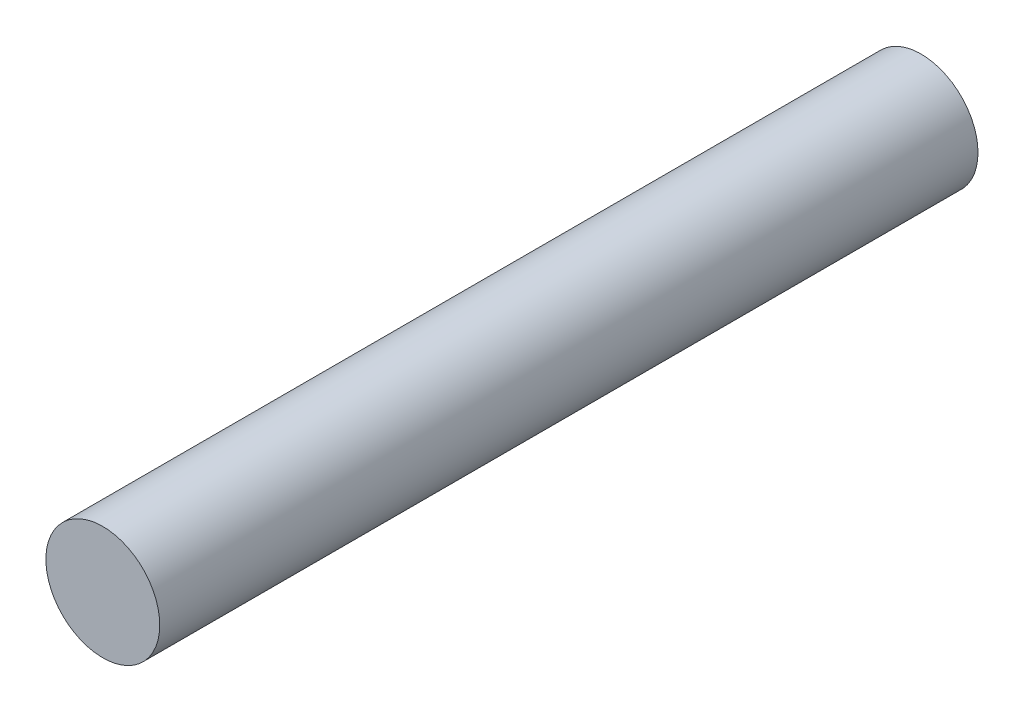
SolidWorks part; units mm, degrees
ref_plane "Front Plane" through (0, 0, 0) normal (0, 0, 1) x (1, 0, 0)
ref_plane "Top Plane" through (0, 0, 0) normal (0, 1, 0) x (1, 0, 0)
ref_plane "Right Plane" through (0, 0, 0) normal (1, 0, 0) x (0, 0, -1)
sketch "Sketch1" plane through (0, 0, 0) normal (0, 0, 1) x (1, 0, 0)
  circle A0 centre (0, 0) radius 3.2
  dimension "D1" = 6.4
extrude "Boss-Extrude1" add sketch "Sketch1" along normal blind 46
scale "缩放比例1" scale about centroid uniform scaling yes scale factor 2
